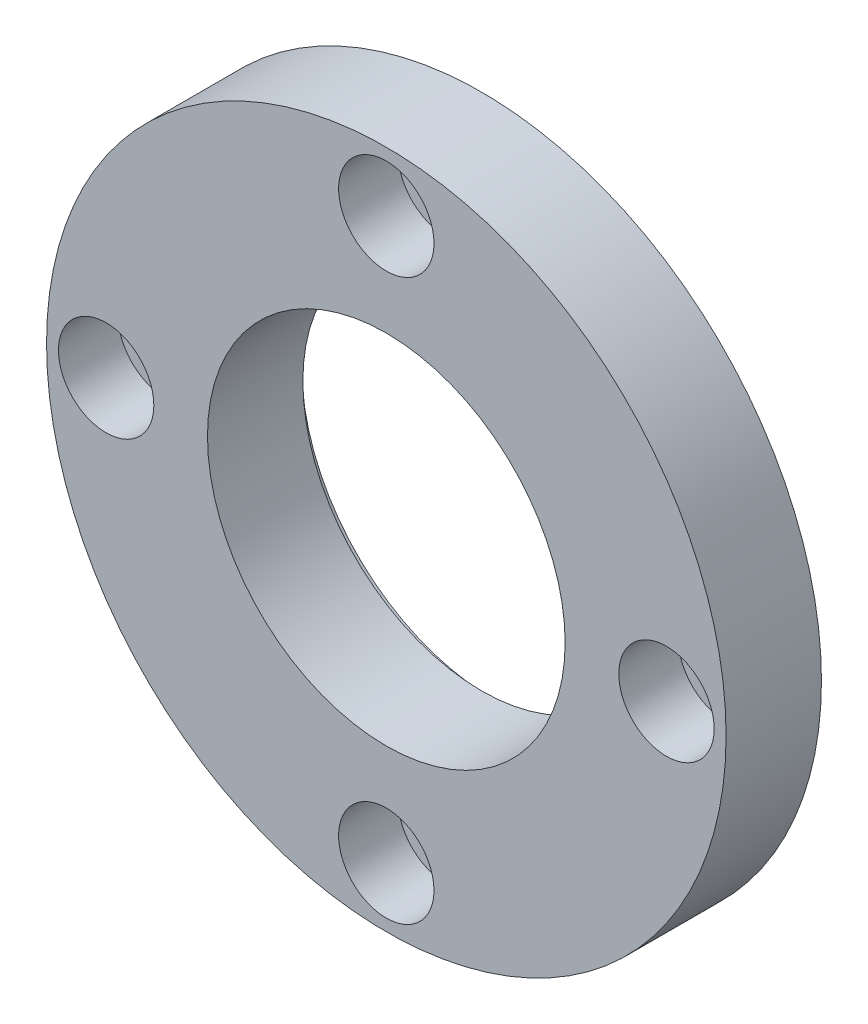
SolidWorks part; units mm, degrees
ref_plane "前视基准面" through (0, 0, 0) normal (0, 0, 1) x (1, 0, 0)
ref_plane "上视基准面" through (0, 0, 0) normal (0, 1, 0) x (1, 0, 0)
ref_plane "右视基准面" through (0, 0, 0) normal (1, 0, 0) x (0, 0, -1)
sketch "草图1" plane through (0, 0, 0) normal (0, 0, 1) x (1, 0, 0)
  circle A0 centre (0, 0) radius 28.5
  circle A1 centre (0, 0) radius 15
  dimension "D1" = 57
  dimension "D2" = 30
extrude "拉伸1" add sketch "草图1" along normal blind 8
sketch "草图2" plane through (0, 0, 0) normal (0, 0, -1) x (-1, 0, 0)
  circle A0 centre (0, 0) radius 18.4
  circle A1 centre (0, 0) radius 16.1
  dimension "D1" = 36.8
  dimension "D2" = 32.2
extrude "拉伸2" add sketch "草图2" along normal blind 1
sketch "草图3" plane through (0, 0, 8) normal (0, 0, 1) x (1, 0, 0)
  line L0 (0, -1000) -> (0, 49000) construction
  line L1 (-1000, 0) -> (49000, 0) construction
  circle A0 centre (0, 23.5) radius 4
  circle A1 centre (-23.5, 0) radius 4
  circle A2 centre (0, -23.5) radius 4
  circle A3 centre (23.5, 0) radius 4
  dimension "D5" = 8
  dimension "D6" = 8
  dimension "D7" = 8
  dimension "D8" = 8
  dimension "D1" = 23.5
  dimension "D2" = 23.5
  dimension "D3" = 23.5
  dimension "D4" = 23.5
extrude "切除-拉伸1" cut sketch "草图3" against normal blind 5
sketch "草图4" plane through (0, 0, 8) normal (0, 0, 1) x (1, 0, 0)
  circle A0 centre (-23.5, 0) radius 2.25
  circle A1 centre (0, 23.5) radius 2.25
  circle A2 centre (23.5, 0) radius 2.25
  circle A3 centre (0, -23.5) radius 2.25
  dimension "D1" = 4.5
extrude "切除-拉伸2" cut sketch "草图4" against normal through all
